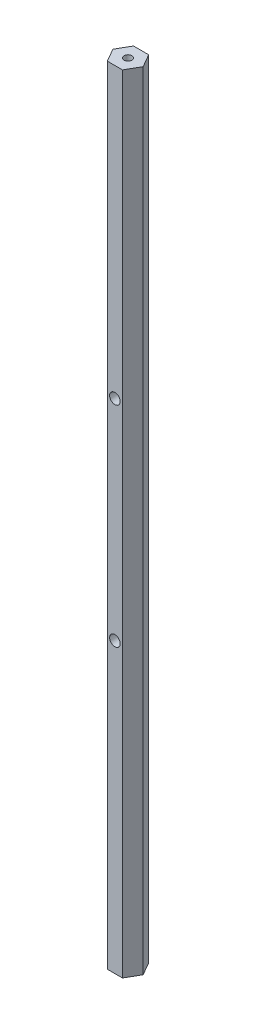
SolidWorks part; units mm, degrees
material "AISI 304"
ref_plane "Front Plane" through (0, 0, 0) normal (0, 0, 1) x (1, 0, 0)
ref_plane "Top Plane" through (0, 0, 0) normal (0, 1, 0) x (1, 0, 0)
ref_plane "Right Plane" through (0, 0, 0) normal (1, 0, 0) x (0, 0, -1)
sketch "Sketch1" plane through (0, 0, 0) normal (0, 1, 0) x (1, 0, 0)
  line L1 (7.3323, 0) -> (3.6662, 6.35)
  line L2 (3.6662, 6.35) -> (-3.6662, 6.35)
  line L3 (-3.6662, 6.35) -> (-7.3323, 0)
  line L4 (-7.3323, 0) -> (-3.6662, -6.35)
  line L5 (-3.6662, -6.35) -> (3.6662, -6.35)
  line L6 (3.6662, -6.35) -> (7.3323, 0)
  circle A0 centre (0, 0) radius 6.35 construction
  dimension "D1" = 12.7
extrude "Boss-Extrude1" add sketch "Sketch1" along normal blind 381
hole_wizard "Tap Drill for #10-24 Tap1" positions "Sketch3" profile "Sketch2" hole size "#10-24" standard "ANSI Inch"
sketch "Sketch3" plane through (0, 381, 0) normal (0, 1, 0) x (1, 0, 0)
  point P0 (0, 0)
sketch "Sketch2" plane through (0, 381, 0) normal (1, 0, 0) x (0, 0, 1)
  line L0 (0, 0) -> (0, 26.5408)
  line L1 (0, 26.5408) -> (1.8986, 25.4)
  line L2 (1.8986, 25.4) -> (1.8986, 0)
  line L5 (1.8986, 0) -> (0, 0)
  line L10 (0, 26.5408) -> (-1.8987, 25.4) construction
  line L11 (0, -6.35) -> (0, 107.95) construction
  dimension "Hole Dia." = 3.7973
  dimension "Hole Depth" = 25.4
  dimension "Drill Angle" = 118
ref_plane "Plane1" through (0, 190.5, 0) normal (0, 1, 0) x (1, 0, 0)
mirror "Mirror1" about plane through (0, 190.5, 0) normal (0, 1, 0) of "Tap Drill for #10-24 Tap1"
hole_wizard "#10 Clearance Hole1" positions "Sketch4" profile "Sketch6" hole size "#10" standard "ANSI Inch" end condition through all
sketch "Sketch4" plane through (0, 0, -6.35) normal (0, 0, -1) x (-1, 0, 0)
  line L0 (-3.6662, 0) -> (3.6662, 0) construction
  line L1 (-3.6662, 190.5) -> (3.6662, 190.5) construction
  line L2 (-3.6662, 381) -> (-3.6662, 0) construction
  line L3 (3.6662, 381) -> (3.6662, 0) construction
  point P0 (0, 139.7)
  point P2 (0, 241.3)
  point P7 (0, 0)
  point P16 (0, 0)
  dimension "D1" = 101.6
sketch "Sketch6" plane through (0, 139.7, -6.35) normal (1, 0, 0) x (0, 1, 0)
  line L0 (0, 0) -> (0, 12.7)
  line L1 (0, 12.7) -> (2.5527, 12.7)
  line L2 (2.5527, 12.7) -> (2.5527, 0)
  line L5 (2.5527, 0) -> (0, 0)
  line L11 (0, -6.35) -> (0, 107.95) construction
  dimension "Thru Hole Dia." = 5.1054
  dimension "Thru Hole Depth" = 12.7
